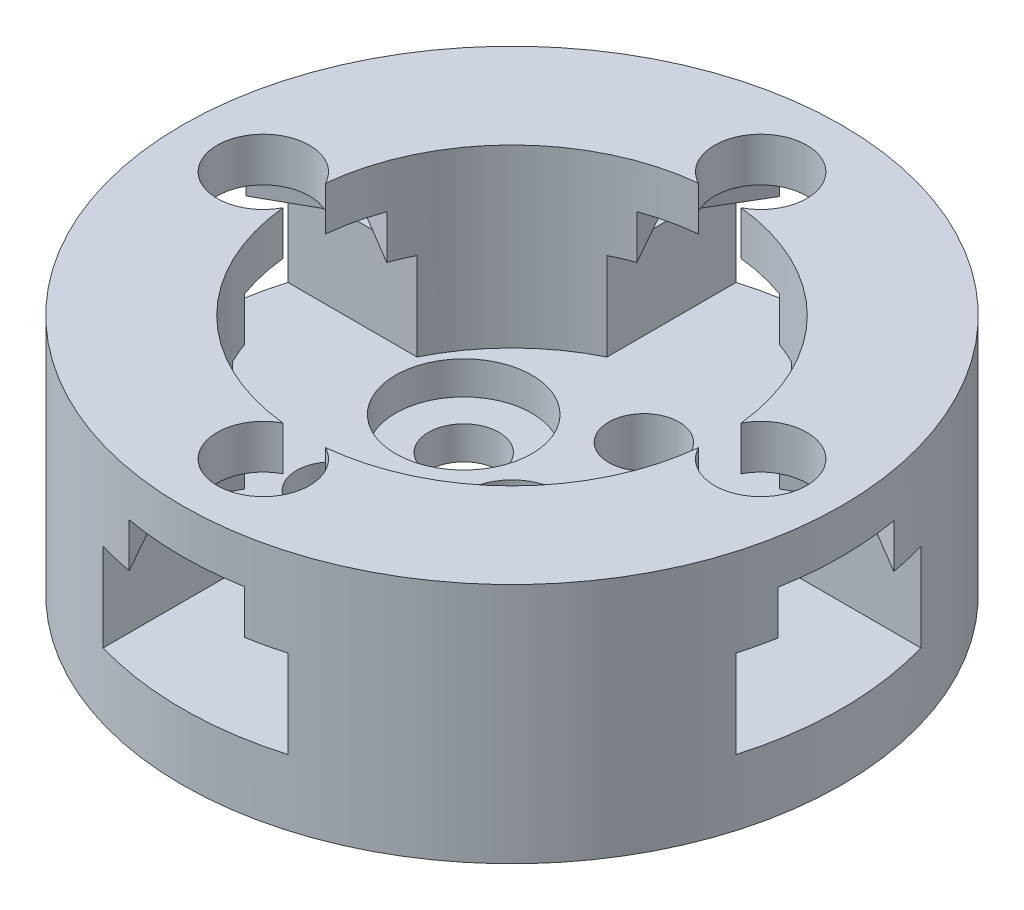
SolidWorks part; units mm, degrees
ref_plane "前视基准面" through (0, 0, 0) normal (0, 0, 1) x (1, 0, 0)
ref_plane "上视基准面" through (0, 0, 0) normal (0, 1, 0) x (1, 0, 0)
ref_plane "右视基准面" through (0, 0, 0) normal (1, 0, 0) x (0, 0, -1)
sketch "Sketch1" plane through (0, 0, 0) normal (0, 1, 0) x (1, 0, 0)
  line L0 (0, 11.2998) -> (0, -11.3131) construction
  circle A0 centre (0, 0) radius 10
  circle A1 centre (0, 0) radius 6 construction
  circle A2 centre (0, 6) radius 1.6
  circle A3 centre (5.1962, 3) radius 1.6
  circle A4 centre (5.1962, -3) radius 1.6
  circle A5 centre (0, -6) radius 1.6
  circle A6 centre (-5.1962, -3) radius 1.6
  circle A7 centre (-5.1962, 3) radius 1.6
  circle A8 centre (0, 0) radius 2.15
  dimension "D1" = 20
  dimension "D2" = 12
  dimension "D3" = 3.2
  dimension "D5" = 4.3
  dimension "D4" = 6
extrude "Boss-Extrude1" add sketch "Sketch1" along normal blind 3
sketch "Sketch2" plane through (0, 3, 0) normal (0, 1, 0) x (1, 0, 0)
  line L0 (0, 10.3978) -> (0, -10.7765) construction
  circle A0 centre (-5.1962, 3) radius 3.1
  circle A3 centre (5.1962, -3) radius 3.1
  circle A6 centre (0, 0) radius 6 construction
  circle A7 centre (0, 6) radius 3.1 [skipped]
  circle A8 centre (0, -6) radius 3.1 [skipped]
  circle A9 centre (-5.1962, -3) radius 3.1 [skipped]
  circle A10 centre (5.1962, 3) radius 3.1 [skipped]
  point P16 (0, 0)
  dimension "D1" = 6.2
  dimension "D2" = 6
extrude "Cut-Extrude2" cut sketch "Sketch2" against normal blind 1.5
sketch "Sketch3" plane through (0, 0, 0) normal (0, -1, 0) x (1, 0, 0)
  circle A0 centre (0, 0) radius 9.5
  circle A1 centre (0, 0) radius 15
  dimension "D1" = 30
  dimension "D2" = 19
extrude "Boss-Extrude2" add sketch "Sketch3" against normal blind 11
sketch "Sketch5" plane through (0, 11, 0) normal (0, 1, 0) x (1, 0, 0)
  line L0 (0, 16.1958) -> (0, -15.6011) construction
  line L1 (11.3137, 0) -> (0, 11.3137) construction
  line L2 (0, 11.3137) -> (-11.3137, 0) construction
  line L3 (-11.3137, 0) -> (0, -11.3137) construction
  line L4 (0, -11.3137) -> (11.3137, 0) construction
  circle A0 centre (0, 0) radius 8 construction
  circle A1 centre (0, 11.3137) radius 2.1
  circle A2 centre (11.3137, 0) radius 2.1
  circle A3 centre (0, -11.3137) radius 2.1
  circle A4 centre (-11.3137, 0) radius 2.1
  point P19 (0, 0)
  dimension "D1" = 16
  dimension "D2" = 4.2
  dimension "D3" = 4
extrude "Cut-Extrude3" cut sketch "Sketch5" against normal blind 4
sketch "Sketch7" plane through (0, 7, 0) normal (0, 1, 0) x (1, 0, 0)
  line L0 (0, 15.5155) -> (0, -16.6788) construction
  line L1 (-19.046, 0) -> (22.9688, 0) construction
  line L2 (-17.3137, 4.2) -> (-7.3137, 4.2)
  line L3 (-7.3137, 4.2) -> (-7.3137, -4.2)
  line L4 (-17.3137, 4.2) -> (-17.3137, -4.2)
  line L5 (-17.3137, -4.2) -> (-7.3137, -4.2)
  line L6 (4.2, 7.3137) -> (-4.2, 7.3137)
  line L7 (-4.2, 17.3137) -> (-4.2, 7.3137)
  line L8 (4.2, 17.3137) -> (-4.2, 17.3137)
  line L9 (4.2, 17.3137) -> (4.2, 7.3137)
  line L10 (7.3137, -4.2) -> (7.3137, 4.2)
  line L11 (17.3137, 4.2) -> (7.3137, 4.2)
  line L12 (17.3137, -4.2) -> (17.3137, 4.2)
  line L13 (17.3137, -4.2) -> (7.3137, -4.2)
  line L14 (-4.2, -7.3137) -> (4.2, -7.3137)
  line L15 (4.2, -17.3137) -> (4.2, -7.3137)
  line L16 (-4.2, -17.3137) -> (4.2, -17.3137)
  line L17 (-4.2, -17.3137) -> (-4.2, -7.3137)
  circle A0 centre (-11.3137, 0) radius 0.5 construction
  point P10 (-7.3137, 0)
  point P11 (-17.3137, 0)
  point P26 (0, 0)
  dimension "D5" = 1
  dimension "D1" = 4
  dimension "D2" = 4.2
  dimension "D3" = 10
  dimension "D4" = 4
extrude "Cut-Extrude4" cut sketch "Sketch7" against normal blind 4
sketch "Sketch8" plane through (0, 7, 0) normal (0, -1, 0) x (1, 0, 0)
  line L0 (-2.2576, 7.2843) -> (2.3608, 7.3438)
  line L1 (-7.2843, -2.2576) -> (-7.3438, 2.3608)
  line L2 (-7.3438, 2.3608) -> (-11.3733, 4.6184)
  line L3 (-11.3733, 4.6184) -> (-15.3432, 2.2576)
  line L4 (-15.3432, 2.2576) -> (-15.2836, -2.3608)
  line L5 (-15.2836, -2.3608) -> (-11.2542, -4.6184)
  line L6 (-11.2542, -4.6184) -> (-7.2843, -2.2576)
  line L7 (2.3608, 7.3438) -> (4.6184, 11.3733)
  line L8 (4.6184, 11.3733) -> (2.2576, 15.3432)
  line L9 (2.2576, 15.3432) -> (-2.3608, 15.2836)
  line L10 (-2.3608, 15.2836) -> (-4.6184, 11.2542)
  line L11 (-4.6184, 11.2542) -> (-2.2576, 7.2843)
  line L12 (7.2843, 2.2576) -> (7.3438, -2.3608)
  line L13 (7.3438, -2.3608) -> (11.3733, -4.6184)
  line L14 (11.3733, -4.6184) -> (15.3432, -2.2576)
  line L15 (15.3432, -2.2576) -> (15.2836, 2.3608)
  line L16 (15.2836, 2.3608) -> (11.2542, 4.6184)
  line L17 (11.2542, 4.6184) -> (7.2843, 2.2576)
  line L18 (2.2576, -7.2843) -> (-2.3608, -7.3438)
  line L19 (-2.3608, -7.3438) -> (-4.6184, -11.3733)
  line L20 (-4.6184, -11.3733) -> (-2.2576, -15.3432)
  line L21 (-2.2576, -15.3432) -> (2.3608, -15.2836)
  line L22 (2.3608, -15.2836) -> (4.6184, -11.2542)
  line L23 (4.6184, -11.2542) -> (2.2576, -7.2843)
  circle A0 centre (-11.3137, 0) radius 4 construction
  point P30 (0, 0)
  dimension "D1" = 8
  dimension "D2" = 4
extrude "Cut-Extrude6" cut sketch "Sketch8" against normal blind 2
